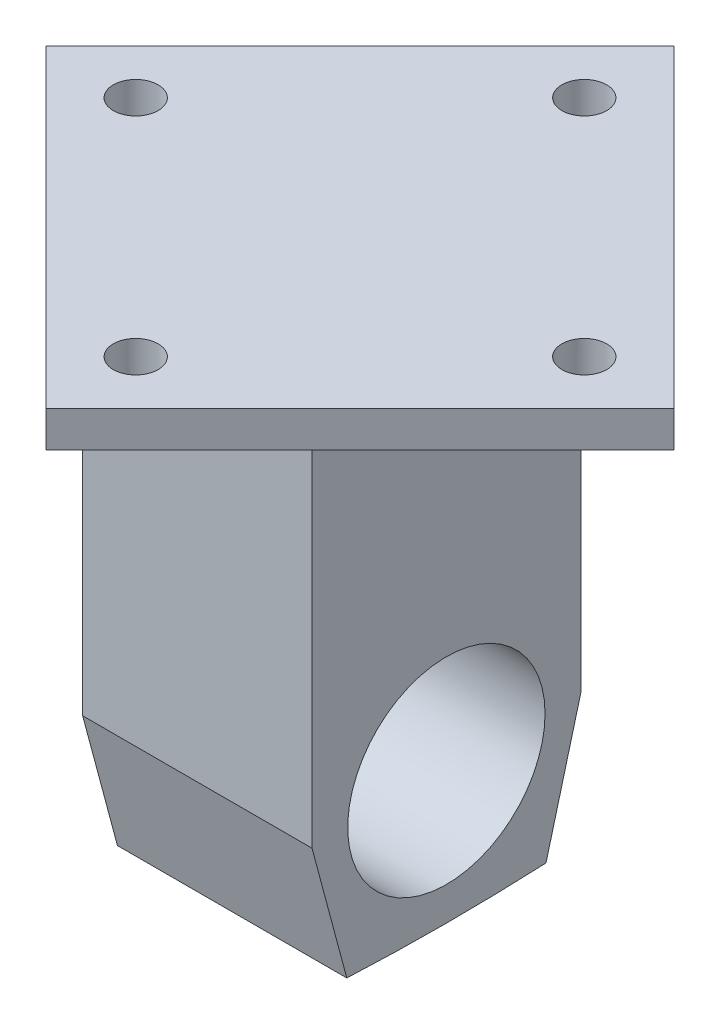
SolidWorks part; units mm, degrees
material "ABS"
ref_plane "Front Plane" through (0, 0, 0) normal (0, 0, 1) x (1, 0, 0)
ref_plane "Top Plane" through (0, 0, 0) normal (0, 1, 0) x (1, 0, 0)
ref_plane "Right Plane" through (0, 0, 0) normal (1, 0, 0) x (0, 0, -1)
sketch "Sketch1" plane through (0, 0, 0) normal (0, 1, 0) x (1, 0, 0)
  line L1 (-16.256, -19.05) -> (16.256, -19.05)
  line L2 (-16.256, -19.05) -> (-16.256, 19.05)
  line L3 (-16.256, 19.05) -> (16.256, 19.05)
  line L4 (16.256, -19.05) -> (16.256, 19.05)
  line L5 (-16.256, -19.05) -> (16.256, 19.05) construction
  line L6 (-16.256, 19.05) -> (16.256, -19.05) construction
  point P0 (0, 0)
extrude "Boss-Extrude1" add sketch "Sketch1" along normal blind 50.292
sketch "Sketch2" plane through (16.256, 0, 0) normal (1, 0, 0) x (0, 0, -1)
  line L0 (-19.05, 0) -> (-14.1195, -18.4009)
  line L1 (19.05, 0) -> (14.1195, -18.4009)
  line L2 (-19.05, 0) -> (19.05, 0)
  line L3 (-19.05, 0) -> (19.05, 0) construction
  arc A1 (14.1195, -18.4009) -> (-14.1195, -18.4009) centre (0, 281.2546) cw
  dimension "D1" = 19.05
  dimension "D2" = 19.05
  dimension "D3" = 75
  dimension "D4" = 75
extrude "Boss-Extrude2" add sketch "Sketch2" against normal up to vertex (32.512 mm away) contours L0 A1 L1 L2 up to point (-16.256, 0, -19.05)
sketch "Sketch3" plane through (16.256, 0, 0) normal (1, 0, 0) x (0, 0, -1)
  circle A0 centre (0, 0) radius 13.9872
extrude "Cut-Extrude1" cut sketch "Sketch3" against normal blind 127 contours A0
sketch "Sketch4" plane through (0, 50.292, 0) normal (0, 1, 0) x (1, 0, 0)
  line L5 (-1.2079, 5.2168) -> (-1.2079, -46.8501) construction
  line L6 (-1.2079, 5.2168) -> (-47.8448, 5.2168) construction
  line L7 (-1.2079, -39.2774) -> (-45.7021, 5.2168)
  line L8 (-45.7021, 5.2168) -> (-1.2079, 49.7109)
  line L9 (-1.2079, 49.7109) -> (43.2862, 5.2168)
  line L10 (43.2862, 5.2168) -> (-1.2079, -39.2774)
extrude "Boss-Extrude3" add sketch "Sketch4" along normal blind 5.08
sketch "Sketch5" plane through (0, 55.372, 0) normal (0, 1, 0) x (1, 0, 0)
  line L0 (43.2862, 5.2168) -> (-45.7021, 5.2168) construction
  line L1 (-1.2079, -39.2774) -> (-1.2079, 49.7109) construction
  circle A0 centre (30.5862, 5.2168) radius 3.175
  circle A1 centre (-1.2079, -26.5774) radius 3.175
  circle A2 centre (-1.2079, 37.0109) radius 3.175
  circle A3 centre (-33.0021, 5.2168) radius 3.175
  dimension "D2" = 6.35
  dimension "D4" = 6.35
  dimension "D1" = 12.7
  dimension "D3" = 12.7
extrude "Cut-Extrude2" cut sketch "Sketch5" against normal through all
